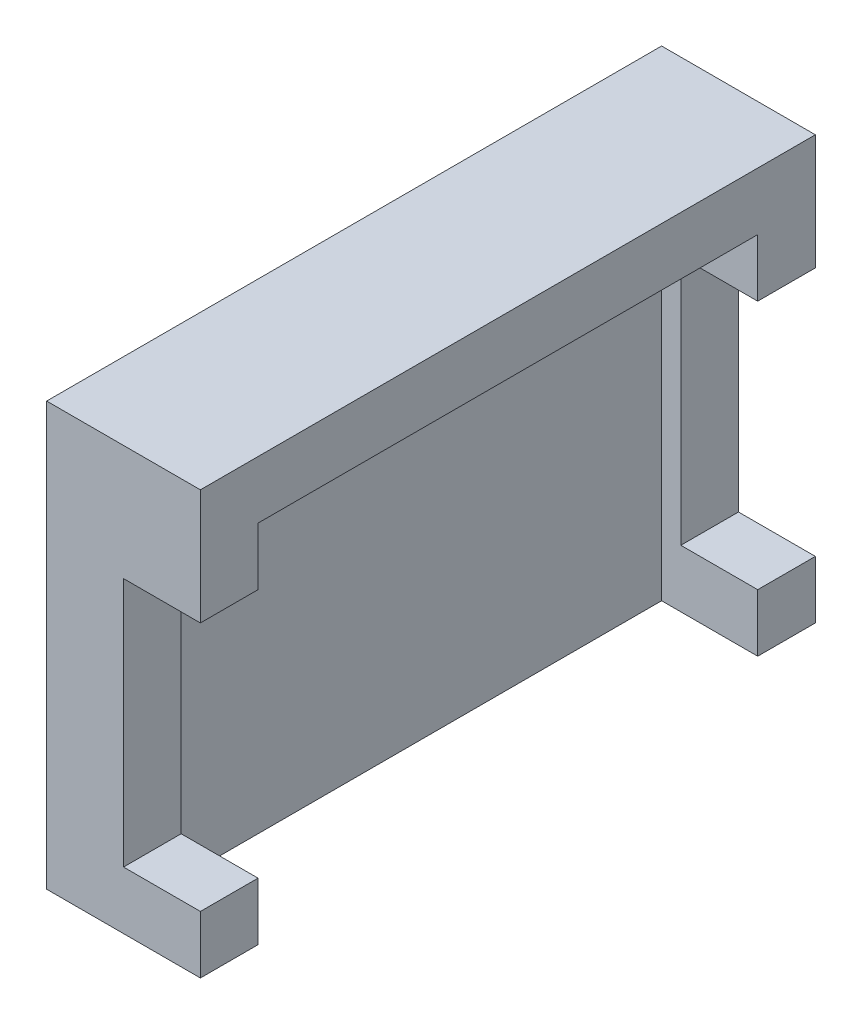
SolidWorks part; units mm, degrees
ref_plane "Front Plane" through (0, 0, 0) normal (0, 0, 1) x (1, 0, 0)
ref_plane "Top Plane" through (0, 0, 0) normal (0, 1, 0) x (1, 0, 0)
ref_plane "Right Plane" through (0, 0, 0) normal (1, 0, 0) x (0, 0, -1)
sketch "Sketch1" plane through (0, 0, 0) normal (1, 0, 0) x (0, 0, -1)
  line L1 (-16, 11) -> (16, 11)
  line L2 (-16, 11) -> (-16, -11)
  line L3 (-16, -11) -> (16, -11)
  line L4 (16, 11) -> (16, -11)
  line L5 (-16, 11) -> (16, -11) construction
  line L6 (-16, -11) -> (16, 11) construction
  point P0 (0, 0)
extrude "Boss-Extrude1" add sketch "Sketch1" along normal blind 3
sketch "Sketch7" plane through (3, 0, 0) normal (1, 0, 0) x (0, 0, -1)
  line L0 (16, -11) -> (16, 11)
  line L1 (16, 11) -> (-16, 11)
  line L2 (-16, 11) -> (-16, -11)
  line L3 (-16, 11) -> (-16, -11) construction
  line L4 (-16, -11) -> (-13, -11)
  line L5 (-16, -11) -> (16, -11) construction
  line L6 (-13, -11) -> (-13, 8)
  line L7 (-13, 8) -> (13, 8)
  line L8 (13, 8) -> (13, -11)
  line L9 (13, -11) -> (16, -11)
  dimension "D1" = 3
  dimension "D2" = 3
  dimension "D3" = 3
extrude "Boss-Extrude6" add sketch "Sketch7" along normal blind 5
sketch "Sketch8" plane through (0, 0, 16) normal (0, 0, 1) x (1, 0, 0)
  line L0 (8, 11) -> (8, -11) construction
  line L1 (8, 5) -> (4, 5)
  line L2 (8, 5) -> (8, -8)
  line L3 (8, -8) -> (4, -8)
  line L4 (4, 5) -> (4, -8)
  dimension "D1" = 3
extrude "Cut-Extrude3" cut sketch "Sketch8" against normal blind 32
